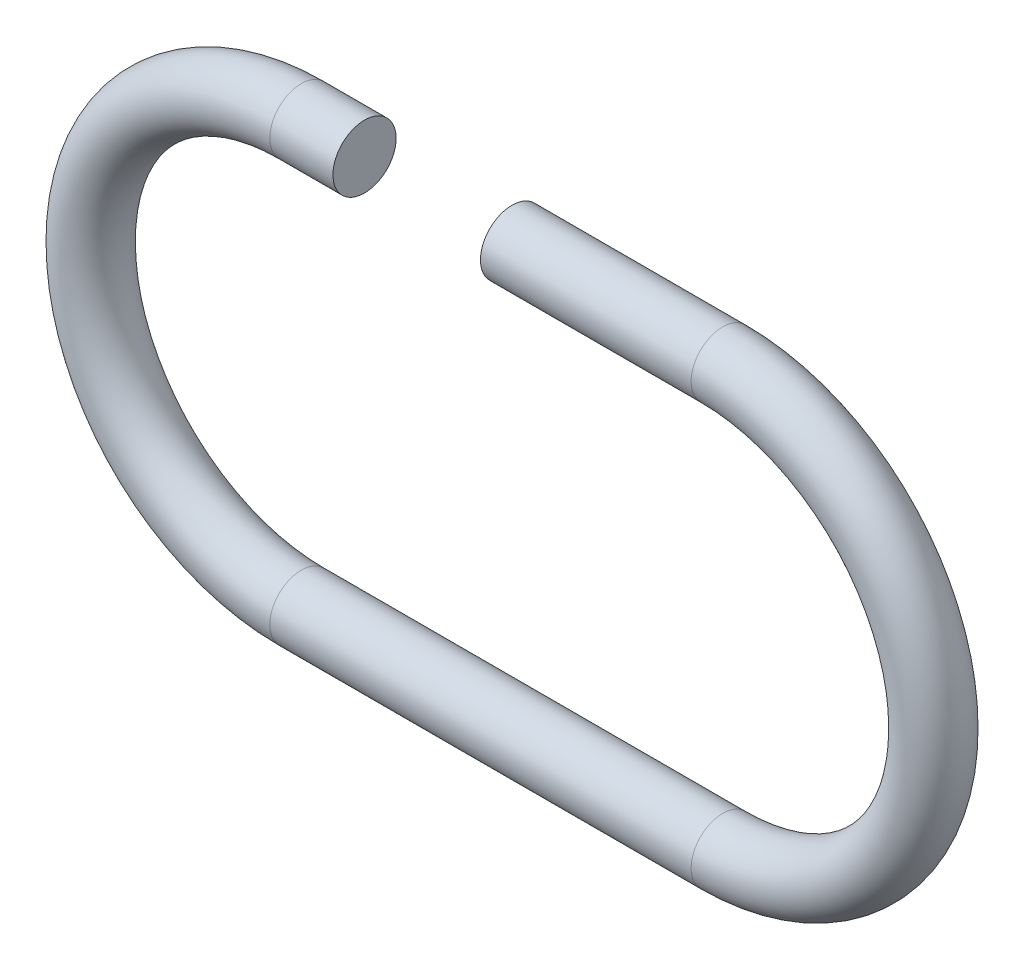
SolidWorks part; units mm, degrees
ref_plane "Front Plane" through (0, 0, 0) normal (0, 0, 1) x (1, 0, 0)
ref_plane "Top Plane" through (0, 0, 0) normal (0, 1, 0) x (1, 0, 0)
ref_plane "Right Plane" through (0, 0, 0) normal (1, 0, 0) x (0, 0, -1)
sketch "Sketch1" plane through (0, 0, 0) normal (1, 0, 0) x (0, 0, -1)
  circle A0 centre (0, 0) radius 1.5
  dimension "D1" = 3
sketch "Sketch2" plane through (0, 0, 0) normal (0, 0, 1) x (1, 0, 0)
  line L0 (0, 0) -> (10, 0)
  line L1 (10, -20) -> (-10, -20)
  line L2 (-10, 0) -> (-7, 0)
  arc A0 (10, 0) -> (10, -20) centre (10, -10) cw
  arc A1 (-10, -20) -> (-10, 0) centre (-10, -10) cw
  point P8 (-3.1817, 0)
  point P10 (0, 0)
  dimension "D2" = 10
  dimension "D3" = 10
  dimension "D1" = 20
  dimension "D4" = 10
  dimension "D5" = 3
sweep "Sweep1" add profiles "Sketch1" path "Sketch2"
